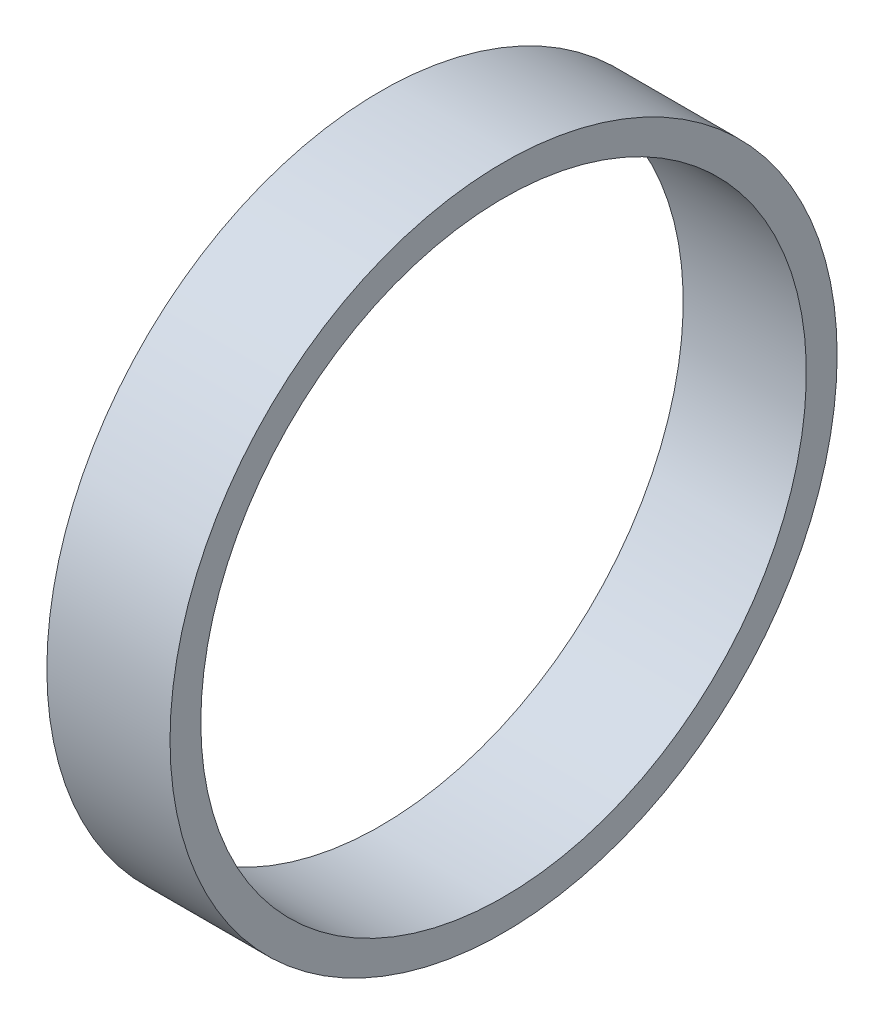
SolidWorks part; units mm, degrees
ref_plane "Front Plane" through (0, 0, 0) normal (0, 0, 1) x (1, 0, 0)
ref_plane "Top Plane" through (0, 0, 0) normal (0, 1, 0) x (1, 0, 0)
ref_plane "Right Plane" through (0, 0, 0) normal (1, 0, 0) x (0, 0, -1)
sketch "Axial profile (mm)" plane through (0, 0, 0) normal (0, 0, 1) x (1, 0, 0)
  line L0 (-110, 0) -> (75, 0) construction
  line L1 (-1.9, 11.8) -> (2.9, 11.8)
  line L2 (2.9, 11.8) -> (2.9, 13)
  line L3 (2.9, 13) -> (-1.9, 13)
  line L4 (-1.9, 13) -> (-1.9, 11.8)
revolve "Full revolution" add sketch "Axial profile (mm)" angle 360 about L0
